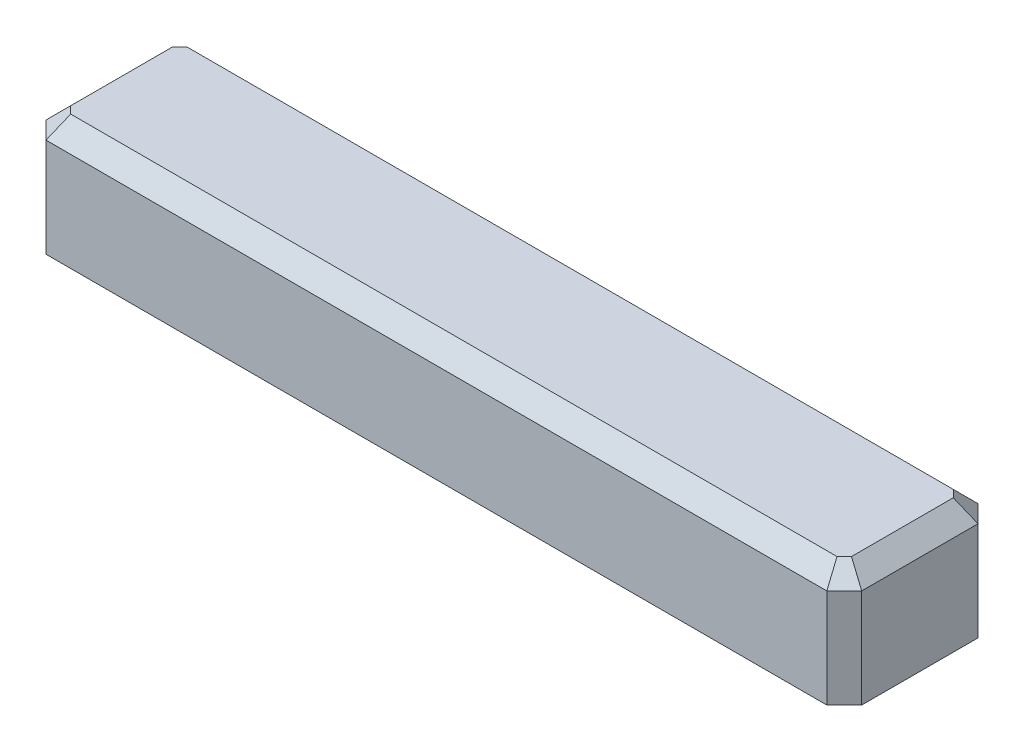
SolidWorks part; units mm, degrees
ref_plane "Front Plane" through (0, 0, 0) normal (0, 0, 1) x (1, 0, 0)
ref_plane "Top Plane" through (0, 0, 0) normal (0, 1, 0) x (1, 0, 0)
ref_plane "Right Plane" through (0, 0, 0) normal (1, 0, 0) x (0, 0, -1)
sketch "Sketch1" plane through (0, 0, 0) normal (0, 1, 0) x (1, 0, 0)
  line L0 (-35.07, 5) -> (-33.57, 6.5)
  line L1 (-33.57, -6.5) -> (33.57, -6.5)
  line L2 (-35.07, -5) -> (-35.07, 5)
  line L3 (-33.57, 6.5) -> (33.57, 6.5)
  line L4 (35.07, -5) -> (35.07, 5)
  line L5 (-35.07, -6.5) -> (35.07, 6.5) construction
  line L6 (-35.07, 6.5) -> (35.07, -6.5) construction
  line L7 (33.57, 6.5) -> (35.07, 5)
  line L8 (-35.07, -5) -> (-33.57, -6.5)
  line L9 (33.57, -6.5) -> (35.07, -5)
  point P0 (0, 0)
  point P10 (0, 0)
  dimension "D1" = 70.14
  dimension "D2" = 13
extrude "Boss-Extrude1" add sketch "Sketch1" along normal blind 10
chamfer "Chamfer1" distance 1.5 angle 45 8 edges at (-35.07, 10, 0) (0, 10, -6.5) (35.07, 10, 0) (0, 10, 6.5) (-34.32, 10, 5.75) (-34.32, 10, -5.75) (34.32, 10, -5.75) (34.32, 10, 5.75)
sketch "Sketch2" plane through (0, 0, 0) normal (0, -1, 0) x (1, 0, 0)
  line L0 (33.57, -6.5) -> (-33.57, -6.5) construction
  line L1 (-30.67, 1.3) -> (30.67, 1.3)
  line L2 (-30.67, 1.3) -> (-30.67, -2.5)
  line L3 (-30.67, -2.5) -> (30.67, -2.5)
  line L4 (30.67, 1.3) -> (30.67, -2.5)
  line L5 (-30.67, 1.3) -> (30.67, -2.5) construction
  line L6 (-30.67, -2.5) -> (30.67, 1.3) construction
  line L7 (35.07, 5) -> (35.07, -5) construction
  line L8 (-35.07, -5) -> (-35.07, 5) construction
  point P4 (0, -0.6)
  point P9 (30.67, -0.6)
  dimension "D1" = 4
  dimension "D2" = 4.4
  dimension "D3" = 4.4
  dimension "D4" = 3.8
extrude "Cut-Extrude1" cut sketch "Sketch2" against normal blind 7
